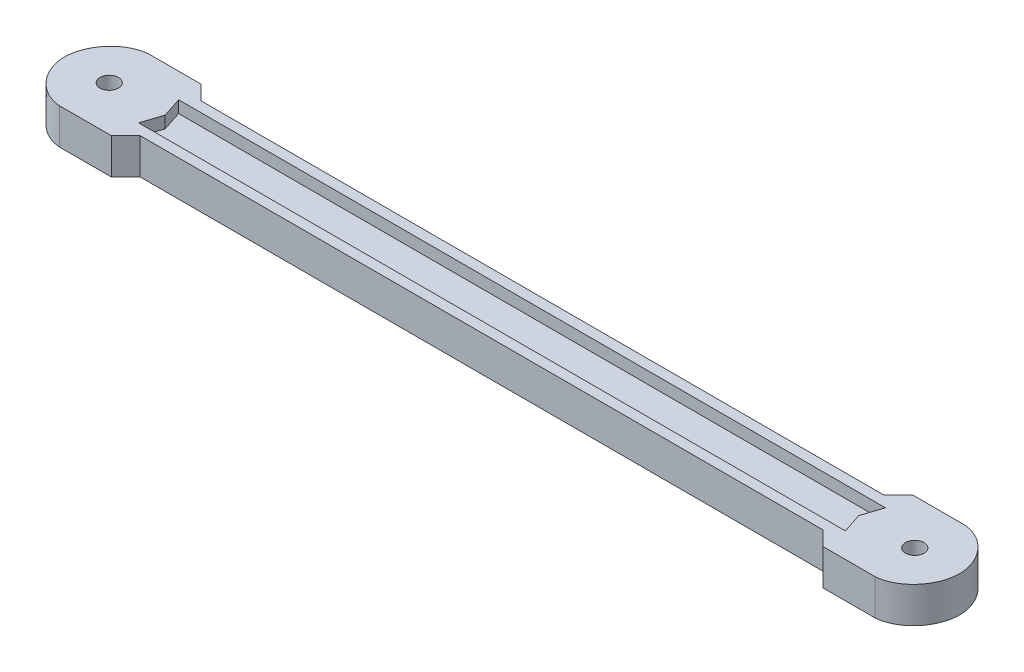
SolidWorks part; units mm, degrees
ref_plane "Plan de face" through (0, 0, 0) normal (0, 0, 1) x (1, 0, 0)
ref_plane "Plan de dessus" through (0, 0, 0) normal (0, 1, 0) x (1, 0, 0)
ref_plane "Plan de droite" through (0, 0, 0) normal (1, 0, 0) x (0, 0, -1)
sketch "Esquisse1" plane through (0, 0, 0) normal (0, 1, 0) x (1, 0, 0)
  line L0 (-75, -7.5) -> (-75, 7.5)
  line L1 (-3.3, 0) -> (3.3, 0) construction
  line L2 (-75, 7.5) -> (75, 7.5)
  line L3 (0, -3.3) -> (0, 3.3) construction
  line L4 (-75, -7.5) -> (75, -7.5)
  line L5 (75, -7.5) -> (75, 7.5)
  point P5 (-75, 0)
  point P6 (75, 0)
  point P10 (0, -7.5)
  point P11 (0, 7.5)
  dimension "D1" = 15
  dimension "D2" = 150
extrude "Boss.-Extru.1" add sketch "Esquisse1" along normal blind 6
sketch "Esquisse2" plane through (0, 0, 0) normal (0, -1, 0) x (1, 0, 0)
  line L0 (3.3, 0) -> (-3.3, 0) construction
  line L1 (0, -3.3) -> (0, 3.3) construction
  line L2 (-75, -7.5) -> (-75, 7.5) construction
  circle A0 centre (-67.5, 0) radius 7.5 construction
  circle A1 centre (67.5, 0) radius 7.5 construction
  dimension "D1" = 7.5
  dimension "D2" = 15
sketch "Esquisse3" plane through (0, 0, 0) normal (0, -1, 0) x (1, 0, 0)
  line L0 (-75, -7.5) -> (-75, 7.5) construction
  line L1 (0, -3.3) -> (0, 3.3) construction
  circle A0 centre (-67.5, 0) radius 1.55
  circle A1 centre (67.5, 0) radius 1.55
  dimension "D1" = 3.1
  dimension "D2" = 7.5
sketch "Esquisse4" plane through (0, 6, 0) normal (0, 1, 0) x (1, 0, 0)
  line L0 (-59.6592, 7.5) -> (-57.2385, 5.0794)
  line L1 (75, 7.5) -> (-75, 7.5) construction
  line L2 (-57.2385, 5.0794) -> (57.2385, 5.0794)
  line L3 (0, -3.3) -> (0, 3.3) construction
  line L4 (-59.6592, 7.5) -> (-67.5, 7.5)
  line L5 (-3.3, 0) -> (3.3, 0) construction
  line L6 (-75, 7.5) -> (-75, -7.5) construction
  line L7 (59.6592, 7.5) -> (67.5, 7.5)
  line L8 (59.6592, 7.5) -> (57.2385, 5.0794)
  line L9 (59.6592, -7.5) -> (57.2385, -5.0794)
  line L10 (59.6592, -7.5) -> (67.5, -7.5)
  line L11 (-59.6592, -7.5) -> (-67.5, -7.5)
  line L12 (-57.2385, -5.0794) -> (57.2385, -5.0794)
  line L13 (-59.6592, -7.5) -> (-57.2385, -5.0794)
  line L15 (-82.8206, 15) -> (82.8206, 15)
  line L16 (-82.8206, 15) -> (-82.8206, -15)
  line L17 (-82.8206, -15) -> (82.8206, -15)
  line L18 (82.8206, 15) -> (82.8206, -15)
  line L19 (-82.8206, 15) -> (82.8206, -15) construction
  line L20 (-82.8206, -15) -> (82.8206, 15) construction
  circle A0 centre (-67.5, 0) radius 7.5 construction
  spline S0 degree 3 poles (-67.5, 7.5) (-71.5852, 7.774) (-78.4148, 0) (-71.5852, -7.774) (-67.5, -7.5) knots 0 0 0 0 0.5 1 1 1 1
  spline S1 degree 3 poles (67.5, 7.5) (71.5852, 7.774) (78.4148, 0) (71.5852, -7.774) (67.5, -7.5) knots 0 0 0 0 0.5 1 1 1 1
  point P28 (0, 5.0794)
  point P42 (0, -5.0794)
  point P43 (0, 0)
  dimension "D1" = 17.7615
  dimension "D4" = 15.3206
  dimension "D2" = 15.3408
  dimension "D3" = 15.3206
  dimension "D5" = 30
  dimension "D6" = 7.5
  dimension "D7" = 7.5
  dimension "D8" = 7.5
  dimension "D9" = 7.5
  dimension "D10" = 7.5
  dimension "D11" = 1.9098
  dimension "D12" = 2.5
extrude "Enlèv. mat.-Extru.1" cut sketch "Esquisse4" against normal blind 12
extrude "Enlèv. mat.-Extru.2" cut sketch "Esquisse3" against normal blind 12
sketch "Esquisse5" plane through (0, 6, 0) normal (0, 1, 0) x (1, 0, 0)
  line L0 (-58.125, 0) -> (-59.2174, 3.3519)
  line L1 (-3.3, 0) -> (3.3, 0) construction
  line L2 (-59.2174, 3.3519) -> (59.2174, 3.3519)
  line L3 (0, -3.3) -> (0, 3.3) construction
  line L4 (-59.2174, -3.3519) -> (59.2174, -3.3519)
  line L5 (-58.125, 0) -> (-59.2174, -3.3519)
  line L6 (58.125, 0) -> (59.2174, -3.3519)
  line L7 (58.125, 0) -> (59.2174, 3.3519)
  line L8 (-57.2385, 5.0794) -> (57.2385, 5.0794) construction
  point P12 (0, -3.3519)
  point P13 (0, 3.3519)
  dimension "D1" = 8.2826
  dimension "D2" = 1.9789
  dimension "D3" = 9.375
  dimension "D4" = 1.7274
extrude "Enlèv. mat.-Extru.3" cut sketch "Esquisse5" against normal blind 2
